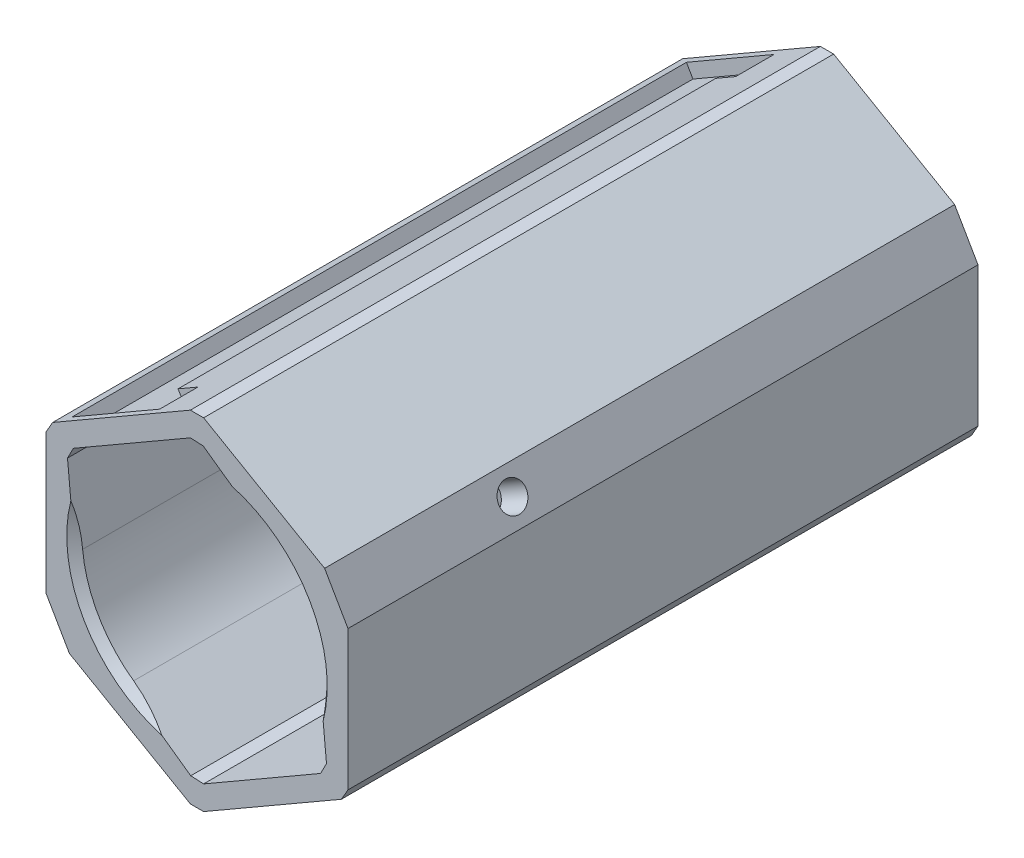
SolidWorks part; units mm, degrees
ref_plane "Front Plane" through (0, 0, 0) normal (0, 0, 1) x (1, 0, 0)
ref_plane "Top Plane" through (0, 0, 0) normal (0, 1, 0) x (1, 0, 0)
ref_plane "Right Plane" through (0, 0, 0) normal (1, 0, 0) x (0, 0, -1)
sketch "Sketch1" plane through (0, 0, 0) normal (0, 1, 0) x (1, 0, 0)
  line L0 (0, -39.84) -> (0, 48.538) construction
  line L1 (-48.4604, 0) -> (48.3051, 0) construction
  line L2 (0, 0) -> (16.125, 0)
  line L3 (16.125, 0) -> (16.125, -71)
  line L4 (16.125, -71) -> (19.65, -71)
  line L5 (19.65, -71) -> (19.65, 68)
  line L6 (19.65, 68) -> (24.95, 68)
  line L7 (24.95, 68) -> (24.95, 73)
  line L8 (24.95, 73) -> (28.1, 73)
  line L9 (28.1, 73) -> (28.1, 68)
  line L10 (28.1, 68) -> (42, 68)
  line L11 (42, 68) -> (42, 76)
  line L12 (42, 76) -> (16.65, 76)
  line L13 (16.65, 76) -> (16.65, 18.0044)
  line L14 (16.65, 18.0044) -> (12.194, 18.0044)
  line L15 (12.194, 18.0044) -> (12.194, 24.8827)
  line L16 (12.194, 24.8827) -> (0, 24.8827)
  line L17 (0, 0) -> (0, 24.8827)
  dimension "D1" = 42
  dimension "D2" = 8
  dimension "D3" = 16.125
  dimension "D4" = 19.65
  dimension "D5" = 71
  dimension "D6" = 68
  dimension "D7" = 5.3
  dimension "D8" = 3
  dimension "D9" = 3.15
  dimension "D10" = 68
  dimension "D11" = 5
revolve "Revolve1" add sketch "Sketch1" angle 360 about L0
sketch "Sketch2" plane through (0, 0, 71) normal (0, 0, 1) x (1, 0, 0)
  line L0 (0, 50.7794) -> (0, -52.6576) construction
  line L2 (0, 22.762) -> (-19.7125, 11.381)
  line L3 (-19.7125, 11.381) -> (-19.7125, -11.381)
  line L4 (-19.7125, -11.381) -> (0, -22.762)
  line L5 (0, -22.762) -> (19.7125, -11.381)
  line L6 (19.7125, -11.381) -> (19.7125, 11.381)
  line L7 (19.7125, 11.381) -> (0, 22.762)
  circle A0 centre (0, 0) radius 16
  circle A1 centre (0, 0) radius 19.7125 construction
  dimension "D1" = 32
  dimension "D2" = 39.425
extrude "Boss-Extrude1" add sketch "Sketch2" against normal blind 82.25
sketch "Sketch3" plane through (0, 0, 0) normal (0, 1, 0) x (1, 0, 0)
  line L0 (19.7125, -71) -> (0, -71) construction
  line L1 (-69.8468, 135.683) -> (82.1728, 135.683)
  line L2 (-69.8468, 135.683) -> (-69.8468, 11.25)
  line L3 (-69.8468, 11.25) -> (82.1728, 11.25)
  line L4 (82.1728, 135.683) -> (82.1728, 11.25)
  dimension "D1" = 82.25
extrude "Cut-Extrude1" cut sketch "Sketch3" against normal through all both and the other way through all
sketch "Sketch4" plane through (-9.8563, 17.0715, 0) normal (-0.5, 0.866, 0) x (0.866, 0.5, 0)
  line L0 (0, 22.8519) -> (0, -81.41) construction
  line L1 (11.381, -71) -> (-11.381, -71) construction
  line L2 (-8.6, 10.2) -> (4.6, 10.2)
  line L3 (-8.6, 10.2) -> (-8.6, -70)
  line L4 (-8.6, -70) -> (4.6, -70)
  line L5 (1.6, 5.2) -> (1.6, -65)
  line L6 (-3.5, 22.8519) -> (-3.5, -78.1641) construction
  line L8 (4.6, 10.2) -> (4.6, 5.2)
  line L9 (4.6, 5.2) -> (1.6, 5.2)
  line L10 (-54.3589, -29.9) -> (49.651, -29.9) construction
  line L11 (1.6, -65) -> (4.6, -65)
  line L12 (4.6, -65) -> (4.6, -70)
  dimension "D1" = 3
  dimension "D2" = 1
  dimension "D3" = 5.1
  dimension "D4" = 5.1
  dimension "D5" = 3.5
  dimension "D6" = 5
  dimension "D7" = 3
  dimension "D8" = 40.1
  dimension "D9" = 40.1
  dimension "D10" = 5
extrude "Cut-Extrude2" cut sketch "Sketch4" against normal blind 1.7
chamfer "Chamfer2" distance 1 6 edges at (0, -22.762, 29.875) (19.7125, -11.381, 29.875) (19.7125, 11.381, 29.875) (0, 22.762, 29.875) (-19.7125, -11.381, 29.875) (-19.7125, 11.381, 29.875)
chamfer "Chamfer3" distance 1 1 edges at (16, 0, 71)
sketch "Sketch5" plane through (0, 0, 71) normal (0, 0, 1) x (1, 0, 0)
  line L0 (0, 29.2623) -> (0, -28.2706) construction
  line L1 (-17, 9.815) -> (-15.9289, -1.507)
  line L8 (0, 19.6299) -> (-17, 9.815)
  line L11 (0, -19.6299) -> (17, -9.815)
  line L14 (-17, 9.815) -> (-17, -9.815) [skipped]
  line L15 (17, 9.815) -> (0, 19.6299) [skipped]
  line L16 (17, -9.815) -> (17, 9.815) [skipped]
  line L17 (-17, -9.815) -> (0, -19.6299) [skipped]
  line L18 (0, 19.6299) -> (9.2695, 13.0413)
  line L19 (0, -19.6299) -> (-9.2695, -13.0413)
  line L20 (17, -9.815) -> (15.9289, 1.507)
  circle A0 centre (0, 0) radius 17 construction
  arc A3 (-9.2695, -13.0413) -> (15.9289, 1.507) centre (0, 0) ccw
  arc A4 (9.2695, 13.0413) -> (-15.9289, -1.507) centre (0, 0) ccw
  dimension "D1" = 34
  dimension "D2" = 32
  dimension "D3" = 19.6299
  dimension "D4" = 19.6299
extrude "Cut-Extrude3" cut sketch "Sketch5" against normal up to surface (71 mm away) up to face at (16, 0, 0)
chamfer "Chamfer4" distance 1 4 edges at (0, -19.6299, 35.5) (17, -9.815, 35.5) (-17, 9.815, 35.5) (0, 19.6299, 35.5)
sketch "Sketch6" plane through (0, 0, -11.25) normal (0, 0, -1) x (-1, 0, 0)
  line L0 (0, 27.8377) -> (0, -30.1469) construction
  line L1 (-27.1417, 0) -> (27.0229, 0) construction
  line L8 (0, 0) -> (-7.289, 12.625) construction
  line L9 (-7.289, 12.625) -> (-14.5781, 0)
  line L10 (-14.5781, 0) -> (-7.289, -12.625)
  line L11 (-7.289, -12.625) -> (7.289, -12.625)
  line L12 (7.289, -12.625) -> (14.5781, 0)
  line L13 (14.5781, 0) -> (7.289, 12.625)
  line L14 (7.289, 12.625) -> (-7.289, 12.625)
  circle A0 centre (0, 0) radius 12.625 construction
  dimension "D1" = 25.25
  dimension "D2" = 30
extrude "Cut-Extrude4" cut sketch "Sketch6" against normal blind 1.2
sketch "Sketch8" plane through (0, 0, -10.05) normal (0, 0, -1) x (-1, 0, 0)
  circle A0 centre (0, 0) radius 2.75
  dimension "D1" = 5.5
extrude "Cut-Extrude5" cut sketch "Sketch8" against normal through all
sketch "Sketch10" plane through (0, 0, 0) normal (0, 0, 1) x (1, 0, 0)
  line L0 (0, 11.9673) -> (0, -9.2947) construction
  line L1 (2.5, 10) -> (-2.5, 10)
  line L2 (-2.5, 10) -> (-2.5, 7.0711)
  line L3 (2.5, 10) -> (2.5, 7.0711)
  arc A0 (-2.5, 7.0711) -> (2.5, 7.0711) centre (0, 0) ccw
  point P9 (0, 10)
  dimension "D1" = 15
  dimension "D2" = 2.5
  dimension "D3" = 10
extrude "Cut-Extrude7" cut sketch "Sketch10" against normal blind 5
chamfer "Chamfer5" distance 0.5 4 edges at (2.5, 8.5355, 0) (0, 10, 0) (-2.5, 8.5355, 0) (0, -7.5, 0)
sketch "Sketch11" plane through (0, 0, 71) normal (0, 0, 1) x (1, 0, 0)
  line L0 (0, 0) -> (19.7125, 11.381) construction
  line L1 (-23.0929, 0) -> (26.2098, 0) construction
  line L2 (0, 0) -> (9.8563, -17.0715) construction
  line L9 (19.7125, 11.381) -> (16.6606, 13.1431)
  line L15 (0, 0) -> (0, 28.1304) construction
  line L16 (16.6606, 13.1431) -> (19.7125, 7.8569)
  line L18 (19.7125, 7.8569) -> (19.7125, 11.381)
  line L23 (-16.6606, -13.1431) -> (-19.7125, -11.381)
  line L24 (-19.7125, -7.8569) -> (-16.6606, -13.1431)
  line L25 (-19.7125, -11.381) -> (-19.7125, -7.8569)
  dimension "D1" = 30
  dimension "D3" = 21
extrude "Cut-Extrude8" cut sketch "Sketch11" against normal through all
sketch "Sketch12" plane through (-18.1865, -10.5, 0) normal (-0.866, -0.5, 0) x (0, 0, 1)
  line L0 (-22.307, 0) -> (76.3649, 0) construction
  line L1 (34, 27.3384) -> (34, -25.0984) construction
  line L2 (71, 18.8465) -> (71, 3.0519) construction
  line L3 (46, 31.7166) -> (46, -26.3202) construction
  circle A0 centre (48, 0) radius 1.8
  dimension "D3" = 3.6
  dimension "D1" = 37
  dimension "D2" = 12
  dimension "D4" = 2
extrude "Cut-Extrude9" cut sketch "Sketch12" against normal blind 4
sketch "Sketch13" plane through (18.1865, 10.5, 0) normal (0.866, 0.5, 0) x (0, 0, -1)
  circle A0 centre (-48, 0) radius 1.8 construction
  circle A1 centre (-48, 0) radius 1.8
extrude "Cut-Extrude10" cut sketch "Sketch13" against normal blind 4
